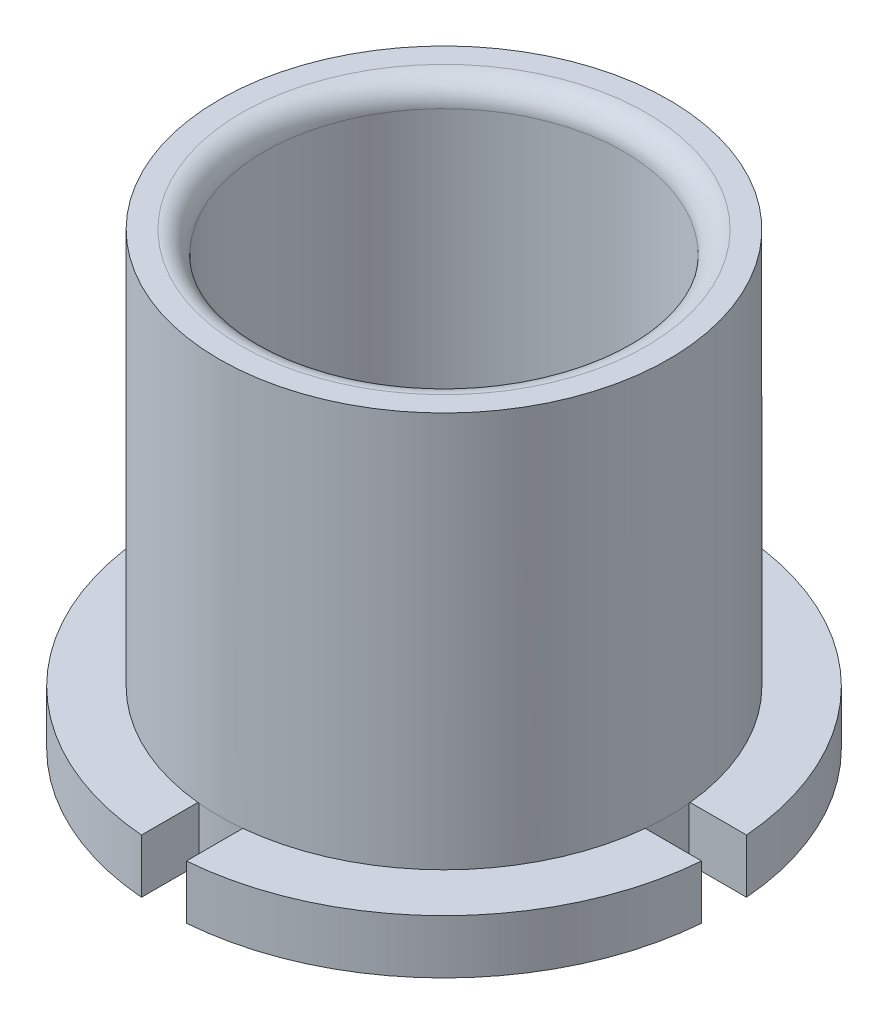
SolidWorks part; units mm, degrees
ref_plane "Front Plane" through (0, 0, 0) normal (0, 0, 1) x (1, 0, 0)
ref_plane "Top Plane" through (0, 0, 0) normal (0, 1, 0) x (1, 0, 0)
ref_plane "Right Plane" through (0, 0, 0) normal (1, 0, 0) x (0, 0, -1)
sketch "Sketch1" plane through (0, 0, 0) normal (0, 1, 0) x (1, 0, 0)
  circle A0 centre (0, 0) radius 10.16
  circle A1 centre (0, 0) radius 12.7
  dimension "D1" = 20.32
  dimension "D2" = 25.4
extrude "Boss-Extrude1" add sketch "Sketch1" along normal blind 25.4
fillet "Fillet1" radius 1.27 1 edges at (0, 25.4, 10.16)
sketch "Sketch2" plane through (0, 0, 0) normal (0, -1, 0) x (1, 0, 0)
  circle A0 centre (0, 0) radius 15.875
  circle A1 centre (0, 0) radius 12.7
  dimension "D1" = 31.75
extrude "Boss-Extrude2" add sketch "Sketch2" against normal blind 3.048
sketch "Sketch3" plane through (0, 3.048, 0) normal (0, 1, 0) x (1, 0, 0)
  line L0 (0, 15.875) -> (0, -15.875) construction
  line L1 (-15.875, 0) -> (15.875, 0) construction
  line L2 (-1.27, 16.3901) -> (-1.27, 12.5801)
  line L4 (1.27, 12.5801) -> (1.27, 16.3901)
  line L5 (1.27, 16.3901) -> (-1.27, 16.3901)
  line L6 (12.5801, -1.27) -> (16.3901, -1.27)
  line L7 (16.3901, -1.27) -> (16.3901, 1.27)
  line L8 (16.3901, 1.27) -> (12.5801, 1.27)
  line L9 (-1.27, -12.5801) -> (-1.27, -16.3901)
  line L10 (-1.27, -16.3901) -> (1.27, -16.3901)
  line L11 (1.27, -16.3901) -> (1.27, -12.5801)
  line L12 (-12.5801, 1.27) -> (-16.3901, 1.27)
  line L13 (-16.3901, 1.27) -> (-16.3901, -1.27)
  line L14 (-16.3901, -1.27) -> (-12.5801, -1.27)
  circle A0 centre (0, 0) radius 15.875 construction
  arc A1 (1.27, 12.5801) -> (-1.27, 12.5801) centre (0, 0) ccw
  arc A2 (12.5801, -1.27) -> (12.5801, 1.27) centre (0, 0) ccw
  arc A3 (-1.27, -12.5801) -> (1.27, -12.5801) centre (0, 0) ccw
  arc A4 (-12.5801, 1.27) -> (-12.5801, -1.27) centre (0, 0) ccw
  dimension "D1" = 1.27
  dimension "D2" = 1.27
  dimension "D3" = 3.81
  dimension "D4" = 4
extrude "Cut-Extrude1" cut sketch "Sketch3" against normal blind 3.048
